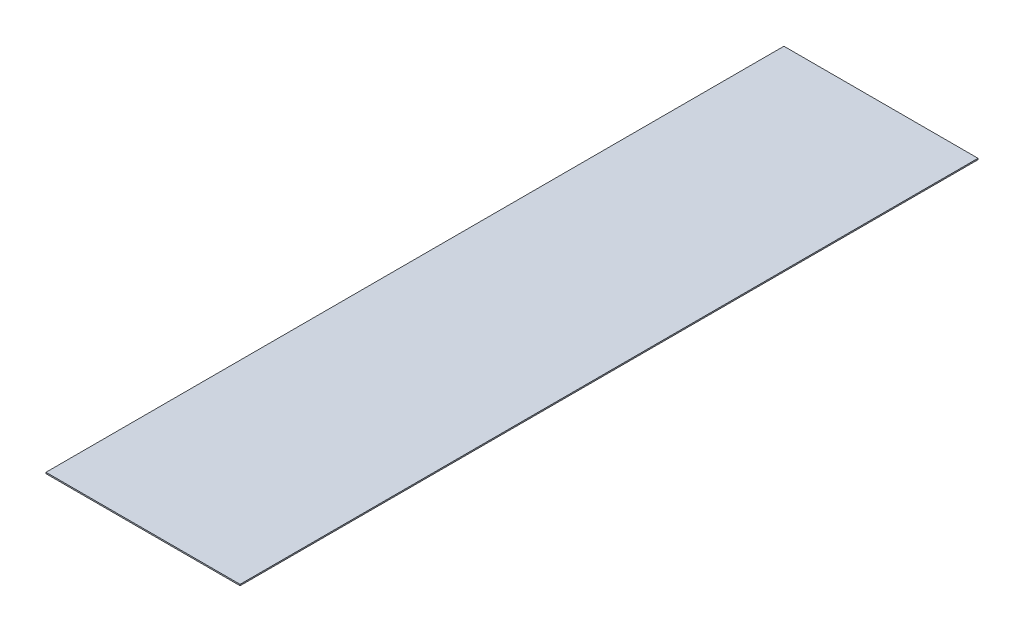
SolidWorks part; units mm, degrees
material "Pine"
ref_plane "Front Plane" through (0, 0, 0) normal (0, 0, 1) x (1, 0, 0)
ref_plane "Top Plane" through (0, 0, 0) normal (0, 1, 0) x (1, 0, 0)
ref_plane "Right Plane" through (0, 0, 0) normal (1, 0, 0) x (0, 0, -1)
sketch "Sketch1" plane through (0, 0, 0) normal (0, 0, 1) x (1, 0, 0)
  line L1 (-240.5063, -1.5875) -> (240.5062, -1.5875)
  line L2 (-240.5063, -1.5875) -> (-240.5063, 1.5875)
  line L3 (-240.5063, 1.5875) -> (240.5062, 1.5875)
  line L4 (240.5062, -1.5875) -> (240.5062, 1.5875)
  line L5 (-240.5063, -1.5875) -> (240.5062, 1.5875) construction
  line L6 (-240.5063, 1.5875) -> (240.5062, -1.5875) construction
  point P0 (0, 0)
  dimension "D1" = 481.0125
  dimension "D2" = 3.175
extrude "Boss-Extrude1" add sketch "Sketch1" along normal blind 1828.8
